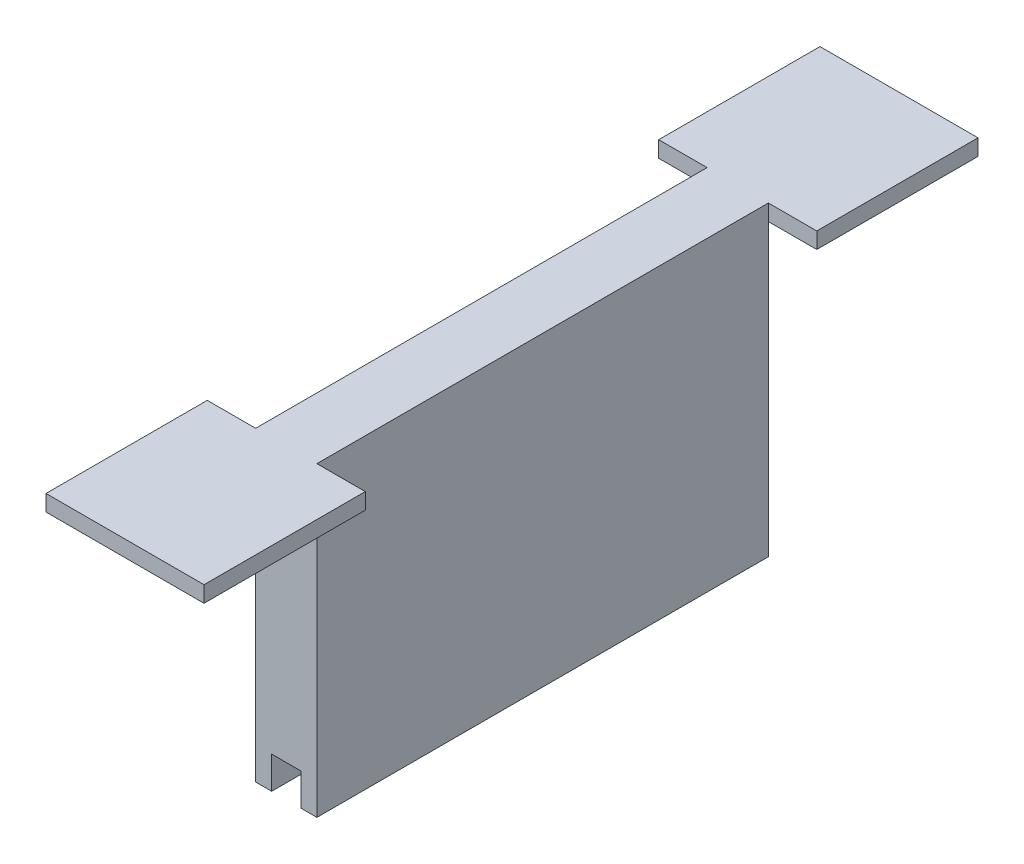
SolidWorks part; units mm, degrees
ref_plane "Front Plane" through (0, 0, 0) normal (0, 0, 1) x (1, 0, 0)
ref_plane "Top Plane" through (0, 0, 0) normal (0, 1, 0) x (1, 0, 0)
ref_plane "Right Plane" through (0, 0, 0) normal (1, 0, 0) x (0, 0, -1)
sketch "Sketch1" plane through (0, 0, 0) normal (0, 0, 1) x (1, 0, 0)
  line L0 (3.8, 0) -> (2.8, 0)
  line L1 (0, 0) -> (3.8, 0)
  line L2 (0, 0) -> (0, 19)
  line L3 (0, 19) -> (3.8, 19)
  line L4 (3.8, 0) -> (3.8, 19)
  line L6 (2.8, 0) -> (0.9953, 0)
  line L7 (2.8, 0) -> (2.8, 2)
  line L8 (2.8, 2) -> (0.9953, 2)
  line L9 (0.9953, 0) -> (0.9953, 2)
  dimension "D1" = 19
  dimension "D2" = 3.8
  dimension "D3" = 1.8047
  dimension "D4" = 2
extrude "Boss-Extrude2" add sketch "Sketch1" along normal blind 28 contours L1 L9 L8 L7 L0 L4 L3 L2
sketch "Sketch3" plane through (0, 0, 28) normal (0, 0, 1) x (1, 0, 0)
  line L0 (3.8, 0) -> (3.8, 19) construction
  line L1 (0, 19) -> (3.8, 19)
  line L2 (0, 19) -> (0, 18)
  line L3 (0, 18) -> (3.8, 18)
  line L4 (3.8, 19) -> (3.8, 18)
  dimension "D1" = 1
extrude "Boss-Extrude3" add sketch "Sketch3" along normal blind 10 contours L2 L1 L4 L3
sketch "Sketch4" plane through (0, 0, 0) normal (0, 0, -1) x (-1, 0, 0)
  line L0 (0, 0) -> (0, 19) construction
  line L1 (-3.8, 19) -> (0, 19)
  line L2 (-3.8, 19) -> (-3.8, 18)
  line L3 (-3.8, 18) -> (0, 18)
  line L4 (0, 19) -> (0, 18)
  dimension "D1" = 1
extrude "Boss-Extrude4" add sketch "Sketch4" along normal blind 10 contours L2 L1 L4 L3
sketch "Sketch5" plane through (3.8, 0, 0) normal (1, 0, 0) x (0, 0, -1)
  line L1 (0, 18) -> (10, 18)
  line L2 (0, 18) -> (0, 19)
  line L3 (0, 19) -> (10, 19)
  line L4 (10, 18) -> (10, 19)
extrude "Boss-Extrude5" add sketch "Sketch5" along normal blind 3 contours L2 L1 L4 L3
sketch "Sketch6" plane through (0, 0, 0) normal (-1, 0, 0) x (0, 0, 1)
  line L1 (0, 18) -> (-10, 18)
  line L2 (0, 18) -> (0, 19)
  line L3 (0, 19) -> (-10, 19)
  line L4 (-10, 18) -> (-10, 19)
extrude "Boss-Extrude6" add sketch "Sketch6" along normal blind 3
sketch "Sketch7" plane through (0, 0, 0) normal (-1, 0, 0) x (0, 0, 1)
  line L1 (28, 18) -> (38, 18)
  line L2 (28, 18) -> (28, 19)
  line L3 (28, 19) -> (38, 19)
  line L4 (38, 18) -> (38, 19)
extrude "Boss-Extrude7" add sketch "Sketch7" along normal blind 3
sketch "Sketch8" plane through (3.8, 0, 0) normal (1, 0, 0) x (0, 0, -1)
  line L1 (-28, 18) -> (-38, 18)
  line L2 (-28, 18) -> (-28, 19)
  line L3 (-28, 19) -> (-38, 19)
  line L4 (-38, 18) -> (-38, 19)
extrude "Boss-Extrude8" add sketch "Sketch8" along normal blind 3
